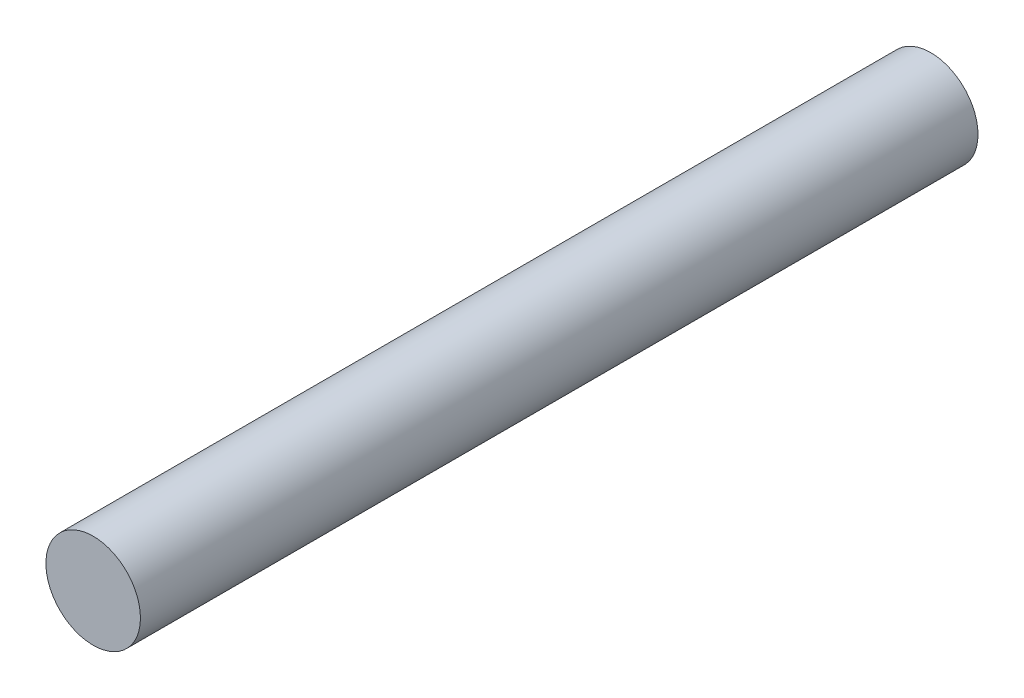
SolidWorks part; units mm, degrees
ref_plane "Front Plane" through (0, 0, 0) normal (0, 0, 1) x (1, 0, 0)
ref_plane "Top Plane" through (0, 0, 0) normal (0, 1, 0) x (1, 0, 0)
ref_plane "Right Plane" through (0, 0, 0) normal (1, 0, 0) x (0, 0, -1)
sketch "Sketch1" plane through (0, 0, 0) normal (0, 0, 1) x (1, 0, 0)
  circle A0 centre (0, 0) radius 2.5
  dimension "D1" = 5
extrude "Boss-Extrude1" add sketch "Sketch1" along normal blind 44.3
